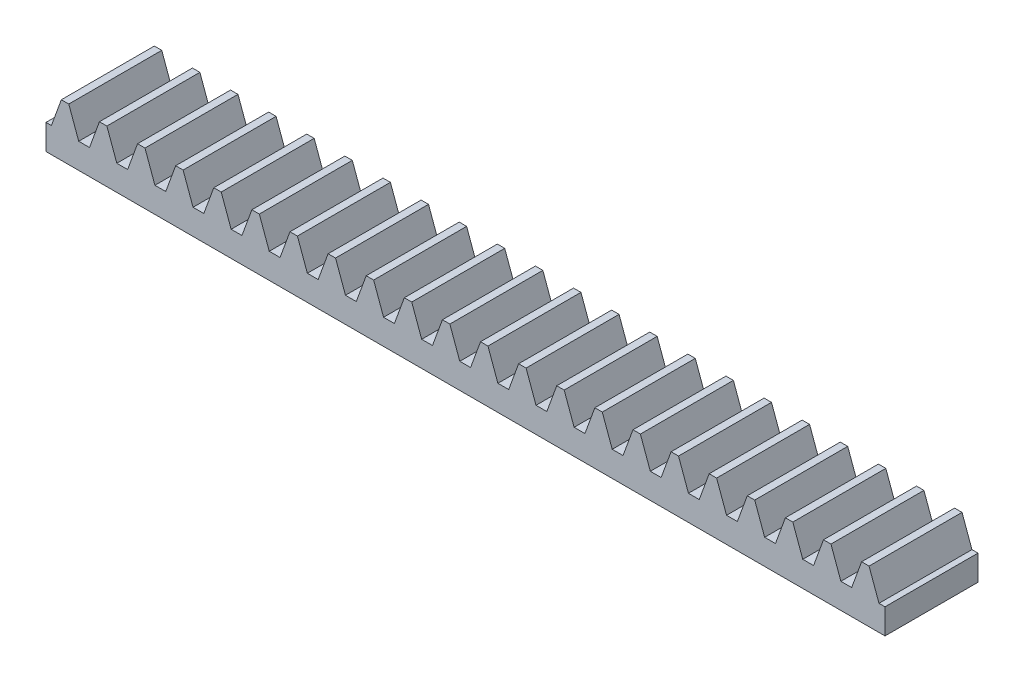
SolidWorks part; units mm, degrees
extrude "Blank" add sketch "BlankSke" against normal blind 5
sketch "BlankSke" plane through (0, 0, 0) normal (0, 0, 1) x (1, 0, 0)
  line L1 (0, 0) -> (41.5, 0)
  line L2 (0, 0) -> (0, 2.6)
  line L3 (0, 2.6) -> (41.5, 2.6)
  line L4 (41.5, 0) -> (41.5, 2.6)
  dimension "Length" = 41.5
  dimension "Blank_height" = 2.6
ref_plane "Plane1" through (0, 0, 0) normal (0, 0, 1) x (1, 0, 0)
ref_plane "Plane2" through (0, 0, 0) normal (0, 1, 0) x (1, 0, 0)
ref_plane "Plane3" through (0, 0, 0) normal (1, 0, 0) x (0, 0, -1)
other "Configuration Table"
sketch "HoldingSke" plane through (0, 0, 0) normal (0, 1, 0) x (1, 0, 0)
  line L0 (0, 0) -> (0.232, 1.6504)
  line L1 (-15, 0) -> (100, 0) construction
  line L2 (0, 0) -> (-2.1039, 2.3779)
  line L3 (0, 0) -> (-11.863, 4.5341)
  line L4 (0, 0) -> (7.8894, 3.5126)
  line L5 (0, 0) -> (-23.7986, -8.8762)
  line L6 (0, 0) -> (-10.5278, -7.1032)
  line L9 (-71.009, 38.7566) -> (-32.0117, 52.9504)
  line L10 (-76.2, 2.9779) -> (-74.2, 2.9779)
  line L11 (0, 0) -> (-5, 0)
  line L12 (-76.2, 101.6) -> (-76.177, 101.6)
  line L13 (24.9733, 27.94) -> (52.9518, 28.4284)
  line L14 (24.9733, 27.94) -> (24.9743, 27.94)
  line L15 (24.9733, 27.94) -> (100.4006, 29.5858)
  circle A0 centre (0, 0) radius 19.05
  circle A1 centre (0, 0) radius 1
  circle A2 centre (0, 0) radius 12.7
  dimension "MPH" = 2
  dimension "Diameter" = 38.1
  dimension "Num_teeth" = 24
  dimension "Pitch" = 1.6667
  dimension "Show_teeth" = 998
  dimension "Thickness" = 12.7
  dimension "Ap" = 20
  dimension "Pitch_height" = 2
  dimension "Width" = 5
  dimension "Backlash" = 0.023
  dimension "Addendum_fac" = 1
  dimension "Dedendum_fac" = 1.25
  dimension "Clearance_fac" = 0.25
  dimension "Dedendum_add" = 0.001
  dimension "Length" = 41.5
  dimension "Module" = 0.6
sketch "TooCutSkeIll" plane through (0, 0, 0) normal (0, 0, 1) x (1, 0, 0)
  line L0 (-0.7529, 2.5842) -> (-0.3034, 1.3494)
  line L1 (-0.1615, 1.25) -> (0.1615, 1.25)
  line L2 (0.3034, 1.3494) -> (0.7529, 2.5842)
  line L3 (41.5, 2.6) -> (0, 2.6) construction
  line L4 (0, 0) -> (0, 64.897) construction
  line L5 (-13.208, 2) -> (12.954, 2) construction
  line L6 (0, 0) -> (41.5, 0) construction
  line L7 (0.5402, 2) -> (0.5402, 48.7463) construction
  line L8 (-0.5402, 2) -> (-0.5402, 48.7463) construction
  line L9 (0.7754, 2.6) -> (0.7754, 2.6254)
  line L10 (-0.7754, 2.6) -> (-0.7754, 2.6254)
  line L11 (-0.7754, 2.6254) -> (0.7754, 2.6254)
  arc A0 (0.1615, 1.25) -> (0.3034, 1.3494) centre (0.1615, 1.401) ccw
  arc A1 (-0.3034, 1.3494) -> (-0.1615, 1.25) centre (-0.1615, 1.401) ccw
  arc A2 (0.7754, 2.6) -> (0.7529, 2.5842) centre (0.7754, 2.576) ccw
  arc A3 (-0.7529, 2.5842) -> (-0.7754, 2.6) centre (-0.7754, 2.576) ccw
  dimension "Pitch_height" = 2
  dimension "Addendum_plus" = 0.6254
  dimension "Pressure_angle" = 20
  dimension "Gap_width" = 1.0805
  dimension "Dedendum" = 0.75
extrude "ToothCutIll" [suppressed] cut sketch "TooCutSkeIll" against normal through all
sketch "TooCutSkeSim" plane through (0, 0, 0) normal (0, 0, 1) x (1, 0, 0)
  line L0 (0.2673, 1.25) -> (-0.2673, 1.25)
  line L1 (0.7679, 2.6254) -> (0.2673, 1.25)
  line L2 (0, 17.4625) -> (0, 53.467) construction
  line L3 (0.7679, 2.6254) -> (-0.7679, 2.6254)
  line L6 (-0.7679, 2.6254) -> (-0.2673, 1.25)
  line L9 (-0.5402, 2) -> (0.5402, 2) construction
  line L10 (0, 0) -> (41.5, 0) construction
  line L11 (0.5402, 2) -> (0.5402, 53.467) construction
  line L12 (-0.5402, 2) -> (-0.5402, 53.467) construction
  dimension "Pitch_height" = 2
  dimension "Addendum_plus" = 0.6254
  dimension "Pressure_angle" = 20
  dimension "Gap_width" = 1.0805
  dimension "Dedendum" = 0.75
extrude "ToothCutSim" cut sketch "TooCutSkeSim" against normal through all
pattern_linear "TeethCuts" count 23 spacing 1.885 along (1, 0, 0) of "ToothCutIll", "ToothCutSim"
sketch "Sketch1" plane through (0, 0, 0) normal (0, 0, 1) x (1, 0, 0)
  line L92 (41.5, 1.25) -> (41.2018, 1.25)
  line L93 (41.2018, 1.25) -> (40.7104, 2.6)
  line L94 (40.7104, 2.6) -> (40.3427, 2.6)
  line L95 (40.3427, 2.6) -> (39.8513, 1.25)
  line L96 (39.8513, 1.25) -> (39.3168, 1.25)
  line L97 (39.3168, 1.25) -> (38.8254, 2.6)
  line L98 (38.8254, 2.6) -> (38.4577, 2.6)
  line L99 (38.4577, 2.6) -> (37.9664, 1.25)
  line L100 (37.9664, 1.25) -> (37.4319, 1.25)
  line L101 (37.4319, 1.25) -> (36.9405, 2.6)
  line L102 (36.9405, 2.6) -> (36.5728, 2.6)
  line L103 (36.5728, 2.6) -> (36.0814, 1.25)
  line L104 (36.0814, 1.25) -> (35.5469, 1.25)
  line L105 (35.5469, 1.25) -> (35.0555, 2.6)
  line L106 (35.0555, 2.6) -> (34.6878, 2.6)
  line L107 (34.6878, 2.6) -> (34.1965, 1.25)
  line L108 (34.1965, 1.25) -> (33.6619, 1.25)
  line L109 (33.6619, 1.25) -> (33.1706, 2.6)
  line L110 (33.1706, 2.6) -> (32.8029, 2.6)
  line L111 (32.8029, 2.6) -> (32.3115, 1.25)
  line L112 (32.3115, 1.25) -> (31.777, 1.25)
  line L113 (31.777, 1.25) -> (31.2856, 2.6)
  line L114 (31.2856, 2.6) -> (30.9179, 2.6)
  line L115 (30.9179, 2.6) -> (30.4266, 1.25)
  line L116 (30.4266, 1.25) -> (29.892, 1.25)
  line L117 (29.892, 1.25) -> (29.4007, 2.6)
  line L118 (29.4007, 2.6) -> (29.033, 2.6)
  line L119 (29.033, 2.6) -> (28.5416, 1.25)
  line L120 (28.5416, 1.25) -> (28.0071, 1.25)
  line L121 (28.0071, 1.25) -> (27.5157, 2.6)
  line L122 (27.5157, 2.6) -> (27.148, 2.6)
  line L123 (27.148, 2.6) -> (26.6566, 1.25)
  line L124 (26.6566, 1.25) -> (26.1221, 1.25)
  line L125 (26.1221, 1.25) -> (25.6308, 2.6)
  line L126 (25.6308, 2.6) -> (25.263, 2.6)
  line L127 (25.263, 2.6) -> (24.7717, 1.25)
  line L128 (24.7717, 1.25) -> (24.2372, 1.25)
  line L129 (24.2372, 1.25) -> (23.7458, 2.6)
  line L130 (23.7458, 2.6) -> (23.3781, 2.6)
  line L131 (23.3781, 2.6) -> (22.8867, 1.25)
  line L132 (22.8867, 1.25) -> (22.3522, 1.25)
  line L133 (22.3522, 1.25) -> (21.8608, 2.6)
  line L134 (21.8608, 2.6) -> (21.4931, 2.6)
  line L135 (21.4931, 2.6) -> (21.0018, 1.25)
  line L136 (21.0018, 1.25) -> (20.4673, 1.25)
  line L137 (20.4673, 1.25) -> (19.9759, 2.6)
  line L138 (19.9759, 2.6) -> (19.6082, 2.6)
  line L139 (19.6082, 2.6) -> (19.1168, 1.25)
  line L140 (19.1168, 1.25) -> (18.5823, 1.25)
  line L141 (18.5823, 1.25) -> (18.0909, 2.6)
  line L142 (18.0909, 2.6) -> (17.7232, 2.6)
  line L143 (17.7232, 2.6) -> (17.2319, 1.25)
  line L144 (17.2319, 1.25) -> (16.6973, 1.25)
  line L145 (16.6973, 1.25) -> (16.206, 2.6)
  line L146 (16.206, 2.6) -> (15.8383, 2.6)
  line L147 (15.8383, 2.6) -> (15.3469, 1.25)
  line L148 (15.3469, 1.25) -> (14.8124, 1.25)
  line L149 (14.8124, 1.25) -> (14.321, 2.6)
  line L150 (14.321, 2.6) -> (13.9533, 2.6)
  line L151 (13.9533, 2.6) -> (13.462, 1.25)
  line L152 (13.462, 1.25) -> (12.9274, 1.25)
  line L153 (12.9274, 1.25) -> (12.4361, 2.6)
  line L154 (12.4361, 2.6) -> (12.0684, 2.6)
  line L155 (12.0684, 2.6) -> (11.577, 1.25)
  line L156 (11.577, 1.25) -> (11.0425, 1.25)
  line L157 (11.0425, 1.25) -> (10.5511, 2.6)
  line L158 (10.5511, 2.6) -> (10.1834, 2.6)
  line L159 (10.1834, 2.6) -> (9.692, 1.25)
  line L160 (9.692, 1.25) -> (9.1575, 1.25)
  line L161 (9.1575, 1.25) -> (8.6662, 2.6)
  line L162 (8.6662, 2.6) -> (8.2984, 2.6)
  line L163 (8.2984, 2.6) -> (7.8071, 1.25)
  line L164 (7.8071, 1.25) -> (7.2726, 1.25)
  line L165 (7.2726, 1.25) -> (6.7812, 2.6)
  line L166 (6.7812, 2.6) -> (6.4135, 2.6)
  line L167 (6.4135, 2.6) -> (5.9221, 1.25)
  line L168 (5.9221, 1.25) -> (5.3876, 1.25)
  line L169 (5.3876, 1.25) -> (4.8962, 2.6)
  line L170 (4.8962, 2.6) -> (4.5285, 2.6)
  line L171 (4.5285, 2.6) -> (4.0372, 1.25)
  line L172 (4.0372, 1.25) -> (3.5026, 1.25)
  line L173 (3.5026, 1.25) -> (3.0113, 2.6)
  line L174 (3.0113, 2.6) -> (2.6436, 2.6)
  line L175 (2.6436, 2.6) -> (2.1522, 1.25)
  line L176 (2.1522, 1.25) -> (1.6177, 1.25)
  line L177 (1.6177, 1.25) -> (1.1263, 2.6)
  line L178 (1.1263, 2.6) -> (0.7586, 2.6)
  line L179 (0.7586, 2.6) -> (0.2673, 1.25)
  line L180 (0.2673, 1.25) -> (0, 1.25)
  line L181 (0, 1.25) -> (0, 0)
  line L182 (0, 0) -> (41.5, 0)
  line L183 (41.5, 0) -> (41.5, 1.25)
  line L184 (41.5, 1.25) -> (41.2018, 1.25)
  line L185 (41.2018, 1.25) -> (40.7104, 2.6)
  line L186 (40.7104, 2.6) -> (40.3427, 2.6)
  line L187 (40.3427, 2.6) -> (39.8513, 1.25)
  line L188 (39.8513, 1.25) -> (39.3168, 1.25)
  line L189 (39.3168, 1.25) -> (38.8254, 2.6)
  line L190 (38.8254, 2.6) -> (38.4577, 2.6)
  line L191 (38.4577, 2.6) -> (37.9664, 1.25)
  line L192 (37.9664, 1.25) -> (37.4319, 1.25)
  line L193 (37.4319, 1.25) -> (36.9405, 2.6)
  line L194 (36.9405, 2.6) -> (36.5728, 2.6)
  line L195 (36.5728, 2.6) -> (36.0814, 1.25)
  line L196 (36.0814, 1.25) -> (35.5469, 1.25)
  line L197 (35.5469, 1.25) -> (35.0555, 2.6)
  line L198 (35.0555, 2.6) -> (34.6878, 2.6)
  line L199 (34.6878, 2.6) -> (34.1965, 1.25)
  line L200 (34.1965, 1.25) -> (33.6619, 1.25)
  line L201 (33.6619, 1.25) -> (33.1706, 2.6)
  line L202 (33.1706, 2.6) -> (32.8029, 2.6)
  line L203 (32.8029, 2.6) -> (32.3115, 1.25)
  line L204 (32.3115, 1.25) -> (31.777, 1.25)
  line L205 (31.777, 1.25) -> (31.2856, 2.6)
  line L206 (31.2856, 2.6) -> (30.9179, 2.6)
  line L207 (30.9179, 2.6) -> (30.4266, 1.25)
  line L208 (30.4266, 1.25) -> (29.892, 1.25)
  line L209 (29.892, 1.25) -> (29.4007, 2.6)
  line L210 (29.4007, 2.6) -> (29.033, 2.6)
  line L211 (29.033, 2.6) -> (28.5416, 1.25)
  line L212 (28.5416, 1.25) -> (28.0071, 1.25)
  line L213 (28.0071, 1.25) -> (27.5157, 2.6)
  line L214 (27.5157, 2.6) -> (27.148, 2.6)
  line L215 (27.148, 2.6) -> (26.6566, 1.25)
  line L216 (26.6566, 1.25) -> (26.1221, 1.25)
  line L217 (26.1221, 1.25) -> (25.6308, 2.6)
  line L218 (25.6308, 2.6) -> (25.263, 2.6)
  line L219 (25.263, 2.6) -> (24.7717, 1.25)
  line L220 (24.7717, 1.25) -> (24.2372, 1.25)
  line L221 (24.2372, 1.25) -> (23.7458, 2.6)
  line L222 (23.7458, 2.6) -> (23.3781, 2.6)
  line L223 (23.3781, 2.6) -> (22.8867, 1.25)
  line L224 (22.8867, 1.25) -> (22.3522, 1.25)
  line L225 (22.3522, 1.25) -> (21.8608, 2.6)
  line L226 (21.8608, 2.6) -> (21.4931, 2.6)
  line L227 (21.4931, 2.6) -> (21.0018, 1.25)
  line L228 (21.0018, 1.25) -> (20.4673, 1.25)
  line L229 (20.4673, 1.25) -> (19.9759, 2.6)
  line L230 (19.9759, 2.6) -> (19.6082, 2.6)
  line L231 (19.6082, 2.6) -> (19.1168, 1.25)
  line L232 (19.1168, 1.25) -> (18.5823, 1.25)
  line L233 (18.5823, 1.25) -> (18.0909, 2.6)
  line L234 (18.0909, 2.6) -> (17.7232, 2.6)
  line L235 (17.7232, 2.6) -> (17.2319, 1.25)
  line L236 (17.2319, 1.25) -> (16.6973, 1.25)
  line L237 (16.6973, 1.25) -> (16.206, 2.6)
  line L238 (16.206, 2.6) -> (15.8383, 2.6)
  line L239 (15.8383, 2.6) -> (15.3469, 1.25)
  line L240 (15.3469, 1.25) -> (14.8124, 1.25)
  line L241 (14.8124, 1.25) -> (14.321, 2.6)
  line L242 (14.321, 2.6) -> (13.9533, 2.6)
  line L243 (13.9533, 2.6) -> (13.462, 1.25)
  line L244 (13.462, 1.25) -> (12.9274, 1.25)
  line L245 (12.9274, 1.25) -> (12.4361, 2.6)
  line L246 (12.4361, 2.6) -> (12.0684, 2.6)
  line L247 (12.0684, 2.6) -> (11.577, 1.25)
  line L248 (11.577, 1.25) -> (11.0425, 1.25)
  line L249 (11.0425, 1.25) -> (10.5511, 2.6)
  line L250 (10.5511, 2.6) -> (10.1834, 2.6)
  line L251 (10.1834, 2.6) -> (9.692, 1.25)
  line L252 (9.692, 1.25) -> (9.1575, 1.25)
  line L253 (9.1575, 1.25) -> (8.6662, 2.6)
  line L254 (8.6662, 2.6) -> (8.2984, 2.6)
  line L255 (8.2984, 2.6) -> (7.8071, 1.25)
  line L256 (7.8071, 1.25) -> (7.2726, 1.25)
  line L257 (7.2726, 1.25) -> (6.7812, 2.6)
  line L258 (6.7812, 2.6) -> (6.4135, 2.6)
  line L259 (6.4135, 2.6) -> (5.9221, 1.25)
  line L260 (5.9221, 1.25) -> (5.3876, 1.25)
  line L261 (5.3876, 1.25) -> (4.8962, 2.6)
  line L262 (4.8962, 2.6) -> (4.5285, 2.6)
  line L263 (4.5285, 2.6) -> (4.0372, 1.25)
  line L264 (4.0372, 1.25) -> (3.5026, 1.25)
  line L265 (3.5026, 1.25) -> (3.0113, 2.6)
  line L266 (3.0113, 2.6) -> (2.6436, 2.6)
  line L267 (2.6436, 2.6) -> (2.1522, 1.25)
  line L268 (2.1522, 1.25) -> (1.6177, 1.25)
  line L269 (1.6177, 1.25) -> (1.1263, 2.6)
  line L270 (1.1263, 2.6) -> (0.7586, 2.6)
  line L271 (0.7586, 2.6) -> (0.2673, 1.25)
  line L272 (0.2673, 1.25) -> (0, 1.25)
  line L273 (0, 1.25) -> (0, 0)
  line L274 (0, 0) -> (41.5, 0)
  line L275 (41.5, 0) -> (41.5, 1.25)
  dimension "D1" = 0
extrude "Cut-Extrude1" cut sketch "Sketch1" against normal blind 0.2
sketch "Sketch2" plane through (0, 0, -5) normal (0, 0, -1) x (-1, 0, 0)
  line L92 (-40.7104, 2.6) -> (-41.2018, 1.25)
  line L93 (-41.2018, 1.25) -> (-41.5, 1.25)
  line L94 (-41.5, 1.25) -> (-41.5, 0)
  line L95 (-41.5, 0) -> (0, 0)
  line L96 (0, 0) -> (0, 1.25)
  line L97 (0, 1.25) -> (-0.2673, 1.25)
  line L98 (-0.2673, 1.25) -> (-0.7586, 2.6)
  line L99 (-0.7586, 2.6) -> (-1.1263, 2.6)
  line L100 (-1.1263, 2.6) -> (-1.6177, 1.25)
  line L101 (-1.6177, 1.25) -> (-2.1522, 1.25)
  line L102 (-2.1522, 1.25) -> (-2.6436, 2.6)
  line L103 (-2.6436, 2.6) -> (-3.0113, 2.6)
  line L104 (-3.0113, 2.6) -> (-3.5026, 1.25)
  line L105 (-3.5026, 1.25) -> (-4.0372, 1.25)
  line L106 (-4.0372, 1.25) -> (-4.5285, 2.6)
  line L107 (-4.5285, 2.6) -> (-4.8962, 2.6)
  line L108 (-4.8962, 2.6) -> (-5.3876, 1.25)
  line L109 (-5.3876, 1.25) -> (-5.9221, 1.25)
  line L110 (-5.9221, 1.25) -> (-6.4135, 2.6)
  line L111 (-6.4135, 2.6) -> (-6.7812, 2.6)
  line L112 (-6.7812, 2.6) -> (-7.2726, 1.25)
  line L113 (-7.2726, 1.25) -> (-7.8071, 1.25)
  line L114 (-7.8071, 1.25) -> (-8.2984, 2.6)
  line L115 (-8.2984, 2.6) -> (-8.6662, 2.6)
  line L116 (-8.6662, 2.6) -> (-9.1575, 1.25)
  line L117 (-9.1575, 1.25) -> (-9.692, 1.25)
  line L118 (-9.692, 1.25) -> (-10.1834, 2.6)
  line L119 (-10.1834, 2.6) -> (-10.5511, 2.6)
  line L120 (-10.5511, 2.6) -> (-11.0425, 1.25)
  line L121 (-11.0425, 1.25) -> (-11.577, 1.25)
  line L122 (-11.577, 1.25) -> (-12.0684, 2.6)
  line L123 (-12.0684, 2.6) -> (-12.4361, 2.6)
  line L124 (-12.4361, 2.6) -> (-12.9274, 1.25)
  line L125 (-12.9274, 1.25) -> (-13.462, 1.25)
  line L126 (-13.462, 1.25) -> (-13.9533, 2.6)
  line L127 (-13.9533, 2.6) -> (-14.321, 2.6)
  line L128 (-14.321, 2.6) -> (-14.8124, 1.25)
  line L129 (-14.8124, 1.25) -> (-15.3469, 1.25)
  line L130 (-15.3469, 1.25) -> (-15.8383, 2.6)
  line L131 (-15.8383, 2.6) -> (-16.206, 2.6)
  line L132 (-16.206, 2.6) -> (-16.6973, 1.25)
  line L133 (-16.6973, 1.25) -> (-17.2319, 1.25)
  line L134 (-17.2319, 1.25) -> (-17.7232, 2.6)
  line L135 (-17.7232, 2.6) -> (-18.0909, 2.6)
  line L136 (-18.0909, 2.6) -> (-18.5823, 1.25)
  line L137 (-18.5823, 1.25) -> (-19.1168, 1.25)
  line L138 (-19.1168, 1.25) -> (-19.6082, 2.6)
  line L139 (-19.6082, 2.6) -> (-19.9759, 2.6)
  line L140 (-19.9759, 2.6) -> (-20.4673, 1.25)
  line L141 (-20.4673, 1.25) -> (-21.0018, 1.25)
  line L142 (-21.0018, 1.25) -> (-21.4931, 2.6)
  line L143 (-21.4931, 2.6) -> (-21.8608, 2.6)
  line L144 (-21.8608, 2.6) -> (-22.3522, 1.25)
  line L145 (-22.3522, 1.25) -> (-22.8867, 1.25)
  line L146 (-22.8867, 1.25) -> (-23.3781, 2.6)
  line L147 (-23.3781, 2.6) -> (-23.7458, 2.6)
  line L148 (-23.7458, 2.6) -> (-24.2372, 1.25)
  line L149 (-24.2372, 1.25) -> (-24.7717, 1.25)
  line L150 (-24.7717, 1.25) -> (-25.263, 2.6)
  line L151 (-25.263, 2.6) -> (-25.6308, 2.6)
  line L152 (-25.6308, 2.6) -> (-26.1221, 1.25)
  line L153 (-26.1221, 1.25) -> (-26.6566, 1.25)
  line L154 (-26.6566, 1.25) -> (-27.148, 2.6)
  line L155 (-27.148, 2.6) -> (-27.5157, 2.6)
  line L156 (-27.5157, 2.6) -> (-28.0071, 1.25)
  line L157 (-28.0071, 1.25) -> (-28.5416, 1.25)
  line L158 (-28.5416, 1.25) -> (-29.033, 2.6)
  line L159 (-29.033, 2.6) -> (-29.4007, 2.6)
  line L160 (-29.4007, 2.6) -> (-29.892, 1.25)
  line L161 (-29.892, 1.25) -> (-30.4266, 1.25)
  line L162 (-30.4266, 1.25) -> (-30.9179, 2.6)
  line L163 (-30.9179, 2.6) -> (-31.2856, 2.6)
  line L164 (-31.2856, 2.6) -> (-31.777, 1.25)
  line L165 (-31.777, 1.25) -> (-32.3115, 1.25)
  line L166 (-32.3115, 1.25) -> (-32.8029, 2.6)
  line L167 (-32.8029, 2.6) -> (-33.1706, 2.6)
  line L168 (-33.1706, 2.6) -> (-33.6619, 1.25)
  line L169 (-33.6619, 1.25) -> (-34.1965, 1.25)
  line L170 (-34.1965, 1.25) -> (-34.6878, 2.6)
  line L171 (-34.6878, 2.6) -> (-35.0555, 2.6)
  line L172 (-35.0555, 2.6) -> (-35.5469, 1.25)
  line L173 (-35.5469, 1.25) -> (-36.0814, 1.25)
  line L174 (-36.0814, 1.25) -> (-36.5728, 2.6)
  line L175 (-36.5728, 2.6) -> (-36.9405, 2.6)
  line L176 (-36.9405, 2.6) -> (-37.4319, 1.25)
  line L177 (-37.4319, 1.25) -> (-37.9664, 1.25)
  line L178 (-37.9664, 1.25) -> (-38.4577, 2.6)
  line L179 (-38.4577, 2.6) -> (-38.8254, 2.6)
  line L180 (-38.8254, 2.6) -> (-39.3168, 1.25)
  line L181 (-39.3168, 1.25) -> (-39.8513, 1.25)
  line L182 (-39.8513, 1.25) -> (-40.3427, 2.6)
  line L183 (-40.3427, 2.6) -> (-40.7104, 2.6)
  line L184 (-40.7104, 2.6) -> (-41.2018, 1.25)
  line L185 (-41.2018, 1.25) -> (-41.5, 1.25)
  line L186 (-41.5, 1.25) -> (-41.5, 0)
  line L187 (-41.5, 0) -> (0, 0)
  line L188 (0, 0) -> (0, 1.25)
  line L189 (0, 1.25) -> (-0.2673, 1.25)
  line L190 (-0.2673, 1.25) -> (-0.7586, 2.6)
  line L191 (-0.7586, 2.6) -> (-1.1263, 2.6)
  line L192 (-1.1263, 2.6) -> (-1.6177, 1.25)
  line L193 (-1.6177, 1.25) -> (-2.1522, 1.25)
  line L194 (-2.1522, 1.25) -> (-2.6436, 2.6)
  line L195 (-2.6436, 2.6) -> (-3.0113, 2.6)
  line L196 (-3.0113, 2.6) -> (-3.5026, 1.25)
  line L197 (-3.5026, 1.25) -> (-4.0372, 1.25)
  line L198 (-4.0372, 1.25) -> (-4.5285, 2.6)
  line L199 (-4.5285, 2.6) -> (-4.8962, 2.6)
  line L200 (-4.8962, 2.6) -> (-5.3876, 1.25)
  line L201 (-5.3876, 1.25) -> (-5.9221, 1.25)
  line L202 (-5.9221, 1.25) -> (-6.4135, 2.6)
  line L203 (-6.4135, 2.6) -> (-6.7812, 2.6)
  line L204 (-6.7812, 2.6) -> (-7.2726, 1.25)
  line L205 (-7.2726, 1.25) -> (-7.8071, 1.25)
  line L206 (-7.8071, 1.25) -> (-8.2984, 2.6)
  line L207 (-8.2984, 2.6) -> (-8.6662, 2.6)
  line L208 (-8.6662, 2.6) -> (-9.1575, 1.25)
  line L209 (-9.1575, 1.25) -> (-9.692, 1.25)
  line L210 (-9.692, 1.25) -> (-10.1834, 2.6)
  line L211 (-10.1834, 2.6) -> (-10.5511, 2.6)
  line L212 (-10.5511, 2.6) -> (-11.0425, 1.25)
  line L213 (-11.0425, 1.25) -> (-11.577, 1.25)
  line L214 (-11.577, 1.25) -> (-12.0684, 2.6)
  line L215 (-12.0684, 2.6) -> (-12.4361, 2.6)
  line L216 (-12.4361, 2.6) -> (-12.9274, 1.25)
  line L217 (-12.9274, 1.25) -> (-13.462, 1.25)
  line L218 (-13.462, 1.25) -> (-13.9533, 2.6)
  line L219 (-13.9533, 2.6) -> (-14.321, 2.6)
  line L220 (-14.321, 2.6) -> (-14.8124, 1.25)
  line L221 (-14.8124, 1.25) -> (-15.3469, 1.25)
  line L222 (-15.3469, 1.25) -> (-15.8383, 2.6)
  line L223 (-15.8383, 2.6) -> (-16.206, 2.6)
  line L224 (-16.206, 2.6) -> (-16.6973, 1.25)
  line L225 (-16.6973, 1.25) -> (-17.2319, 1.25)
  line L226 (-17.2319, 1.25) -> (-17.7232, 2.6)
  line L227 (-17.7232, 2.6) -> (-18.0909, 2.6)
  line L228 (-18.0909, 2.6) -> (-18.5823, 1.25)
  line L229 (-18.5823, 1.25) -> (-19.1168, 1.25)
  line L230 (-19.1168, 1.25) -> (-19.6082, 2.6)
  line L231 (-19.6082, 2.6) -> (-19.9759, 2.6)
  line L232 (-19.9759, 2.6) -> (-20.4673, 1.25)
  line L233 (-20.4673, 1.25) -> (-21.0018, 1.25)
  line L234 (-21.0018, 1.25) -> (-21.4931, 2.6)
  line L235 (-21.4931, 2.6) -> (-21.8608, 2.6)
  line L236 (-21.8608, 2.6) -> (-22.3522, 1.25)
  line L237 (-22.3522, 1.25) -> (-22.8867, 1.25)
  line L238 (-22.8867, 1.25) -> (-23.3781, 2.6)
  line L239 (-23.3781, 2.6) -> (-23.7458, 2.6)
  line L240 (-23.7458, 2.6) -> (-24.2372, 1.25)
  line L241 (-24.2372, 1.25) -> (-24.7717, 1.25)
  line L242 (-24.7717, 1.25) -> (-25.263, 2.6)
  line L243 (-25.263, 2.6) -> (-25.6308, 2.6)
  line L244 (-25.6308, 2.6) -> (-26.1221, 1.25)
  line L245 (-26.1221, 1.25) -> (-26.6566, 1.25)
  line L246 (-26.6566, 1.25) -> (-27.148, 2.6)
  line L247 (-27.148, 2.6) -> (-27.5157, 2.6)
  line L248 (-27.5157, 2.6) -> (-28.0071, 1.25)
  line L249 (-28.0071, 1.25) -> (-28.5416, 1.25)
  line L250 (-28.5416, 1.25) -> (-29.033, 2.6)
  line L251 (-29.033, 2.6) -> (-29.4007, 2.6)
  line L252 (-29.4007, 2.6) -> (-29.892, 1.25)
  line L253 (-29.892, 1.25) -> (-30.4266, 1.25)
  line L254 (-30.4266, 1.25) -> (-30.9179, 2.6)
  line L255 (-30.9179, 2.6) -> (-31.2856, 2.6)
  line L256 (-31.2856, 2.6) -> (-31.777, 1.25)
  line L257 (-31.777, 1.25) -> (-32.3115, 1.25)
  line L258 (-32.3115, 1.25) -> (-32.8029, 2.6)
  line L259 (-32.8029, 2.6) -> (-33.1706, 2.6)
  line L260 (-33.1706, 2.6) -> (-33.6619, 1.25)
  line L261 (-33.6619, 1.25) -> (-34.1965, 1.25)
  line L262 (-34.1965, 1.25) -> (-34.6878, 2.6)
  line L263 (-34.6878, 2.6) -> (-35.0555, 2.6)
  line L264 (-35.0555, 2.6) -> (-35.5469, 1.25)
  line L265 (-35.5469, 1.25) -> (-36.0814, 1.25)
  line L266 (-36.0814, 1.25) -> (-36.5728, 2.6)
  line L267 (-36.5728, 2.6) -> (-36.9405, 2.6)
  line L268 (-36.9405, 2.6) -> (-37.4319, 1.25)
  line L269 (-37.4319, 1.25) -> (-37.9664, 1.25)
  line L270 (-37.9664, 1.25) -> (-38.4577, 2.6)
  line L271 (-38.4577, 2.6) -> (-38.8254, 2.6)
  line L272 (-38.8254, 2.6) -> (-39.3168, 1.25)
  line L273 (-39.3168, 1.25) -> (-39.8513, 1.25)
  line L274 (-39.8513, 1.25) -> (-40.3427, 2.6)
  line L275 (-40.3427, 2.6) -> (-40.7104, 2.6)
  dimension "D1" = 0
extrude "Cut-Extrude2" cut sketch "Sketch2" against normal blind 0.2
equation "' \"Module@HoldingSke\" = 6.35"
equation "' \"Num_teeth@HoldingSke\" = 12"
equation "' \"Ap@HoldingSke\" =  20"
equation "' \"Ap@HoldingSke\" = 20"
equation "' \"Width@HoldingSke\" = 0.25 * 25.4"
equation "' \"Show_teeth@HoldingSke\" = 500"
equation "' \"Backlash@HoldingSke\" = 0.009 * 25.4"
equation "' \"Addendum_fac@HoldingSke\" = 1.0"
equation "' \"Dedendum_fac@HoldingSke\" = 1.25"
equation "' \"Dedendum_add@HoldingSke\" = 0.00005 * 25.4"
equation "' \"Clearance_fac@HoldingSke\" = 0.25"
equation "' \"Pitch_height@HoldingSke\" = 1 * 25.4"
equation "' \"Length@HoldingSke\" = 4.71 * 25.4"
equation "\"Pitch@HoldingSke\" = 1 / \"Module@HoldingSke\""
equation "\"MPH@HoldingSke\" = \"Dedendum_fac@HoldingSke\" / \"Pitch@HoldingSke\" + 2 * \"Dedendum_add@HoldingSke\" + 0.002 * 25.4"
equation "\"MPH@HoldingSke\" = ((sgn( \"MPH@HoldingSke\" - \"Pitch_height@HoldingSke\")+1)*( \"MPH@HoldingSke\" - \"Pitch_height@HoldingSke\"))/2 + \"Pitch_height@HoldingSke\""
equation "\"Blank_height@BlankSke\" = \"Pitch_height@HoldingSke\" + \"Addendum_fac@HoldingSke\"  / \"Pitch@HoldingSke\" "
equation "\"Length@BlankSke\" =  \"Length@HoldingSke\""
equation "\"Face_width@Blank\" = \"Width@HoldingSke\""
equation "\"Pressure_angle@TooCutSkeIll\" = \"Ap@HoldingSke\""
equation "\"Addendum_plus@TooCutSkeIll\" =  \"Addendum_fac@HoldingSke\"  / \"Pitch@HoldingSke\" + 0.001 *25.4"
equation "\"Dedendum@TooCutSkeIll\" = \"Dedendum_fac@HoldingSke\"  / \"Pitch@HoldingSke\""
equation "\"Pitch_height@TooCutSkeIll\" =  \"MPH@HoldingSke\""
equation "\"Gap_width@TooCutSkeIll\" = 3.14159265 / 2 / \"Pitch@HoldingSke\" + 6 * \"Backlash@HoldingSke\""
equation "\"Pressure_angle@TooCutSkeSim\" = \"Ap@HoldingSke\""
equation "\"Addendum_plus@TooCutSkeSim\" =  \"Addendum_fac@HoldingSke\"  / \"Pitch@HoldingSke\" + 0.001 * 25.4"
equation "\"Dedendum@TooCutSkeSim\" = \"Dedendum_fac@HoldingSke\"  / \"Pitch@HoldingSke\""
equation "\"Pitch_height@TooCutSkeSim\" =  \"MPH@HoldingSke\""
equation "\"Gap_width@TooCutSkeSim\" = 3.14159265 / 2 / \"Pitch@HoldingSke\" + 6 * \"Backlash@HoldingSke\""
equation "\"Root_fillet@TooCutSkeIll\" = \"Clearance_fac@HoldingSke\" / \"Pitch@HoldingSke\" + \"Dedendum_add@HoldingSke\""
equation "\"Break_rad@TooCutSkeIll\" = 0.02 / \"Pitch@HoldingSke\" * 2"
equation "\"Linear_pitch@TeethCuts\" = 3.14159265 / \"Pitch@HoldingSke\""
equation "\"Num_teeth@HoldingSke\" = int( ( \"Length@HoldingSke\" + 0 ) / (3.14159265 / \"Pitch@HoldingSke\")) + 0.9999  + 1"
equation " \"Num_teeth@TeethCuts\" = int( \"Show_teeth@HoldingSke\" ) + 1"
equation " \"Num_teeth@TeethCuts\" = ((sgn( \"Num_teeth@TeethCuts\" - \"Num_teeth@HoldingSke\" )-1)*( \"Num_teeth@TeethCuts\" - \"Num_teeth@HoldingSke\" ))/-2+ \"Num_teeth@HoldingSke\""
equation " \"Num_teeth@TeethCuts\" = ((sgn( \"Num_teeth@TeethCuts\" - 2.0)+1)*( \"Num_teeth@TeethCuts\" - 2.0))/2 +2.0"
